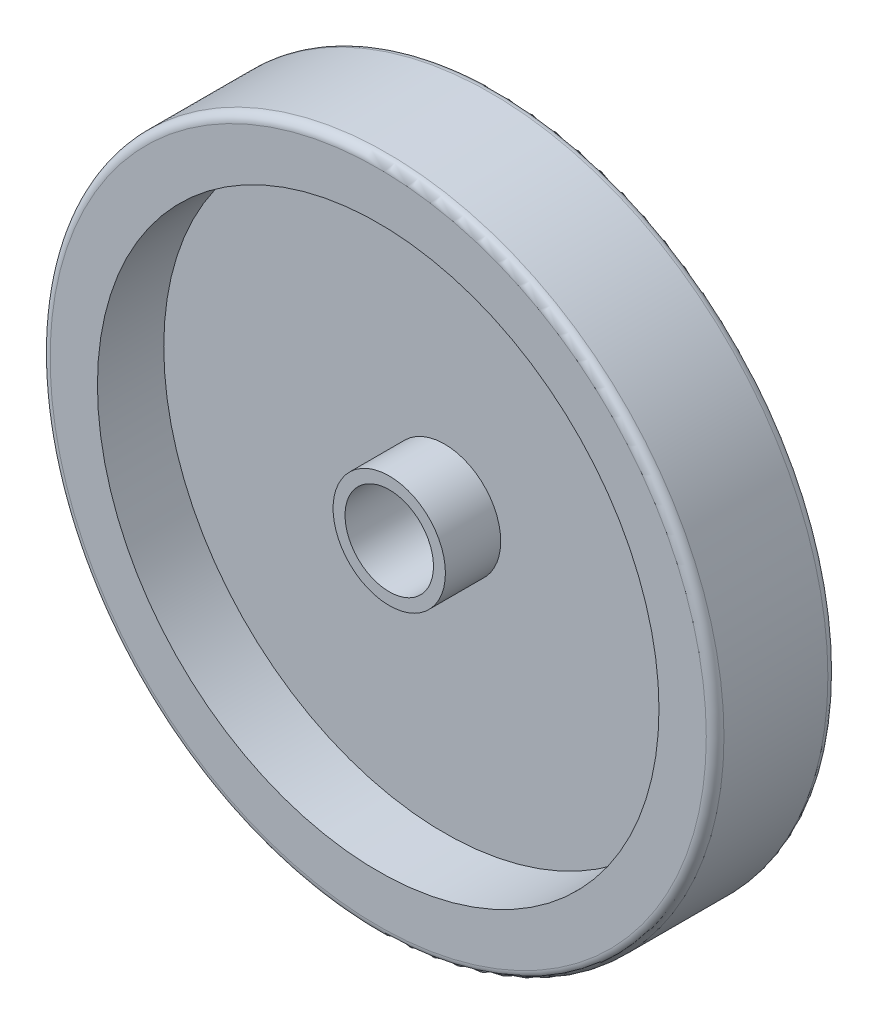
SolidWorks part; units mm, degrees
ref_plane "Front Plane" through (0, 0, 0) normal (0, 0, 1) x (1, 0, 0)
ref_plane "Top Plane" through (0, 0, 0) normal (0, 1, 0) x (1, 0, 0)
ref_plane "Right Plane" through (0, 0, 0) normal (1, 0, 0) x (0, 0, -1)
sketch "Sketch1" plane through (0, 0, 0) normal (0, 0, 1) x (1, 0, 0)
  circle A0 centre (0, 0) radius 76.2
  circle A1 centre (0, 0) radius 10
  circle A2 centre (0, 0) radius 50.8
  dimension "D1" = 152.4
  dimension "D2" = 101.6
extrude "Boss-Extrude2" add sketch "Sketch1" along normal blind 25 contours A2 A1 | A0 A2
sketch "Sketch3" plane through (0, 0, 25) normal (0, 0, 1) x (1, 0, 0)
  line L0 (0, -1000) -> (0, 49000) construction
  line L1 (-1000, 0) -> (49000, 0) construction
  line L2 (0, 0) -> (-53.8815, 53.8815)
  circle A0 centre (0, 0) radius 76.2
  circle A1 centre (0, 0) radius 12.7
  dimension "D1" = 152.4
  dimension "D2" = 25.4
  dimension "D3" = 45
extrude "Cut-Extrude1" cut sketch "Sketch3" against normal mid plane 25
sketch "Sketch4" plane through (0, 0, 12.5) normal (0, 0, 1) x (1, 0, 0)
  circle A0 centre (0, 0) radius 63.5
  circle A1 centre (0, 0) radius 76.2
  dimension "D1" = 127
extrude "Boss-Extrude3" add sketch "Sketch4" along direction (0, 0, 1) on the side of the normal blind 15
fillet "Fillet2" radius 2 2 edges at (76.2, 0, 27.5) (76.2, 0, 0)
